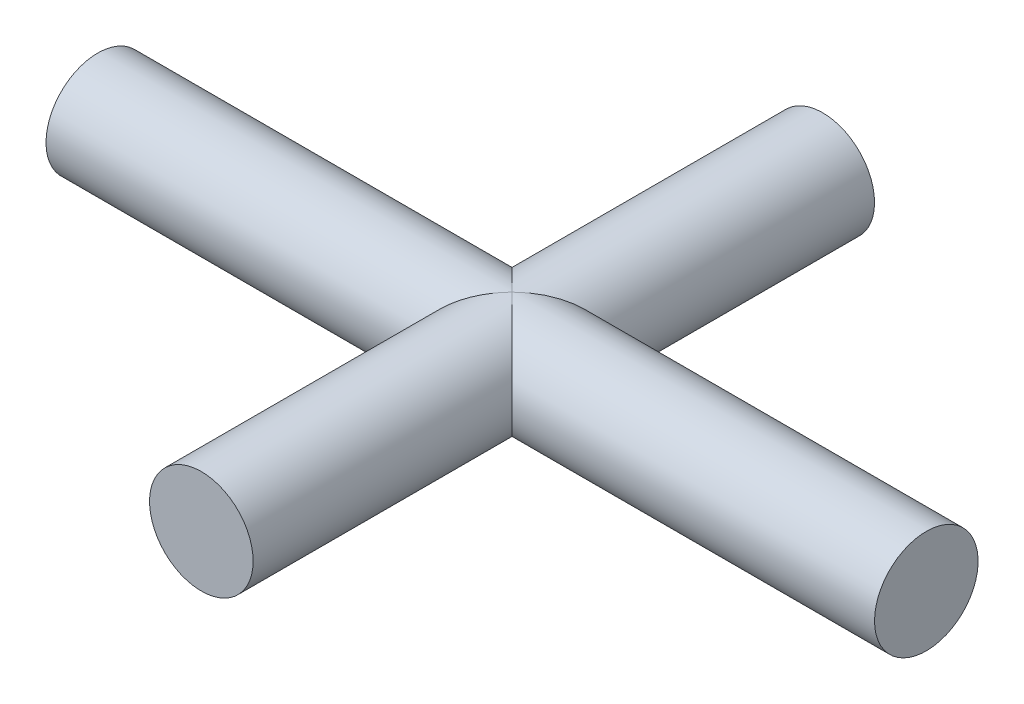
SolidWorks part; units mm, degrees
ref_plane "前视基准面" through (0, 0, 0) normal (0, 0, 1) x (1, 0, 0)
ref_plane "上视基准面" through (0, 0, 0) normal (0, 1, 0) x (1, 0, 0)
ref_plane "右视基准面" through (0, 0, 0) normal (1, 0, 0) x (0, 0, -1)
sketch "草图1" plane through (0, 0, 0) normal (0, 0, 1) x (1, 0, 0)
  line L0 (0, 0) -> (-37.7804, 0) construction
  line L1 (-40, 0) -> (-40, 5)
  line L2 (-40, 5) -> (40, 5)
  line L3 (0, 5) -> (0, 0) construction
  line L4 (40, 0) -> (40, 5)
  line L5 (-40, 0) -> (40, 0)
  line L6 (40, 0) -> (40.1274, 0.04)
  dimension "D1" = 5
  dimension "D2" = 40
revolve "旋转1" add sketch "草图1" angle 360 about L5
sketch "草图2" plane through (0, 0, 0) normal (0, 1, 0) x (1, 0, 0)
  line L0 (0, -30) -> (0, 30)
  line L1 (0, 0) -> (5, 0) construction
  line L2 (5, -30) -> (5, 30)
  line L3 (5, 30) -> (0, 30)
  line L4 (5, -30) -> (0, -30)
  dimension "D1" = 5
  dimension "D2" = 30
revolve "旋转2" add sketch "草图2" angle 360 about L0
